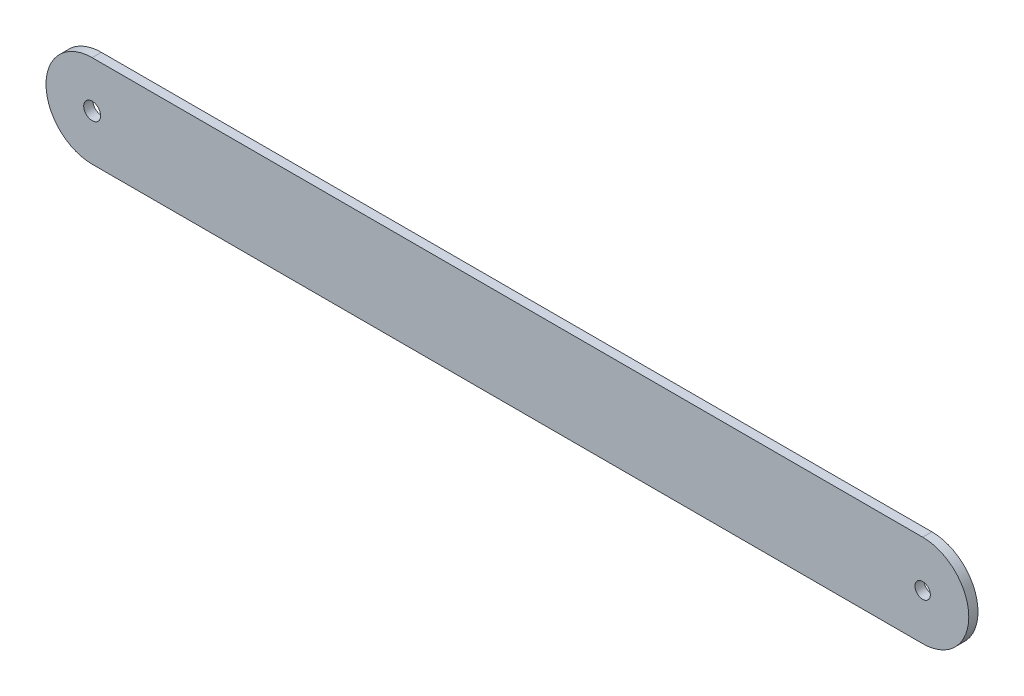
SolidWorks part; units mm, degrees
ref_plane "前视基准面" through (0, 0, 0) normal (0, 0, 1) x (1, 0, 0)
ref_plane "上视基准面" through (0, 0, 0) normal (0, 1, 0) x (1, 0, 0)
ref_plane "右视基准面" through (0, 0, 0) normal (1, 0, 0) x (0, 0, -1)
sketch "草图1" plane through (0, 0, 0) normal (0, 0, 1) x (1, 0, 0)
  line L0 (-15.766, 45.2864) -> (-285.766, 45.2864)
  line L1 (-285.766, 15.2864) -> (-15.766, 15.2864)
  arc A0 (-285.766, 45.2864) -> (-285.766, 15.2864) centre (-285.766, 30.2864) ccw
  circle A1 centre (-285.766, 30.2864) radius 2.75
  arc A2 (-15.766, 15.2864) -> (-15.766, 45.2864) centre (-15.766, 30.2864) ccw
  circle A3 centre (-15.766, 30.2864) radius 2.5
  dimension "D1" = 300
  dimension "D3" = 5.5
  dimension "D4" = 5
  dimension "D2" = 30
extrude "凸台-拉伸1" add sketch "草图1" along normal blind 3
